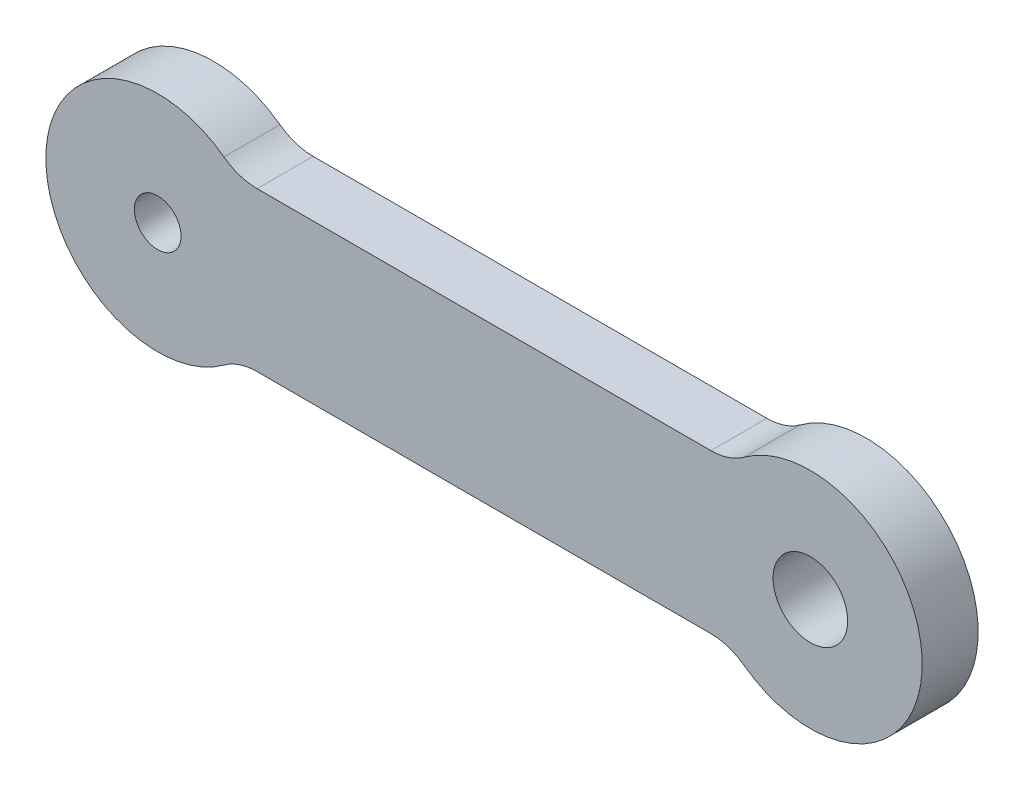
SolidWorks part; units mm, degrees
ref_plane "前视基准面" through (0, 0, 0) normal (0, 0, 1) x (1, 0, 0)
ref_plane "上视基准面" through (0, 0, 0) normal (0, 1, 0) x (1, 0, 0)
ref_plane "右视基准面" through (0, 0, 0) normal (1, 0, 0) x (0, 0, -1)
other "Configuration Table"
sketch "草图1" plane through (0, 0, 0) normal (0, 0, 1) x (1, 0, 0)
  line L0 (0, 0) -> (35, 0) construction
  line L1 (17.5, 0) -> (17.5, 4.25) construction
  line L2 (17.5, 0) -> (17.5, -4.25) construction
  line L3 (29.6673, 4.25) -> (5.3327, 4.25)
  line L4 (29.6673, -4.25) -> (5.3327, -4.25)
  circle A0 centre (0, 0) radius 1.25
  arc A1 (3.5551, 4.8333) -> (3.5551, -4.8333) centre (0, 0) ccw
  arc A2 (5.3327, 4.25) -> (3.5551, 4.8333) centre (5.3327, 7.25) cw
  arc A3 (5.3327, -4.25) -> (3.5551, -4.8333) centre (5.3327, -7.25) ccw
  arc A4 (29.6673, -4.25) -> (31.4449, -4.8333) centre (29.6673, -7.25) cw
  arc A5 (31.4449, 4.8333) -> (31.4449, -4.8333) centre (35, 0) cw
  arc A6 (29.6673, 4.25) -> (31.4449, 4.8333) centre (29.6673, 7.25) ccw
  circle A7 centre (35, 0) radius 2
  dimension "D1" = 3
  dimension "D2" = 2.5
  dimension "D3" = 4
  dimension "D6" = 6
  dimension "D4" = 35
  dimension "D5" = 8.5
extrude "凸台-拉伸1" add sketch "草图1" along normal blind 3
